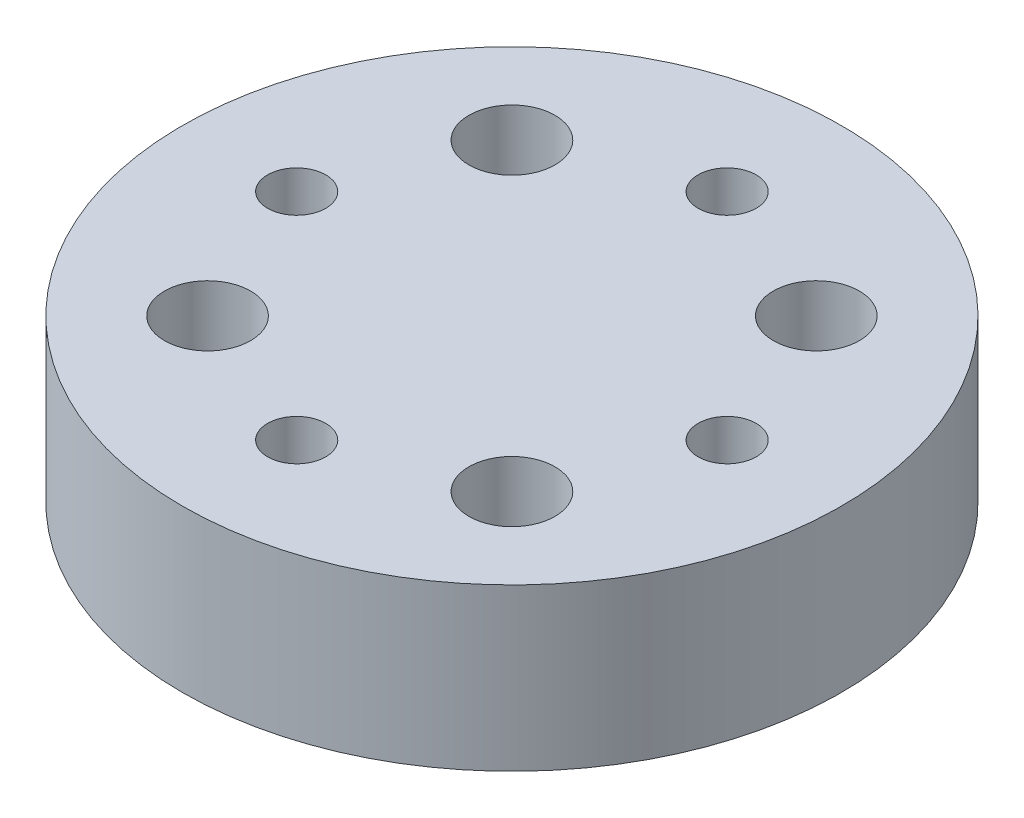
SolidWorks part; units mm, degrees
ref_plane "前视基准面" through (0, 0, 0) normal (0, 0, 1) x (1, 0, 0)
ref_plane "上视基准面" through (0, 0, 0) normal (0, 1, 0) x (1, 0, 0)
ref_plane "右视基准面" through (0, 0, 0) normal (1, 0, 0) x (0, 0, -1)
sketch "草图1" plane through (0, 0, 0) normal (0, 1, 0) x (1, 0, 0)
  line L0 (0, 0) -> (-5.6569, 5.6569) construction
  circle A0 centre (0, 0) radius 8 construction
  circle A1 centre (0, 8) radius 1.08
  circle A2 centre (8, 0) radius 1.08
  circle A3 centre (0, -8) radius 1.08
  circle A4 centre (-8, 0) radius 1.08
  circle A5 centre (-5.6569, 5.6569) radius 1.6
  circle A6 centre (5.6569, 5.6569) radius 1.6
  circle A7 centre (5.6569, -5.6569) radius 1.6
  circle A8 centre (-5.6569, -5.6569) radius 1.6
  circle A9 centre (0, 0) radius 12.25
  point P14 (0, 0)
  point P23 (0, 0)
  dimension "D1" = 4
  dimension "D2" = 4
extrude "凸台-拉伸1" add sketch "草图1" along normal blind 6
